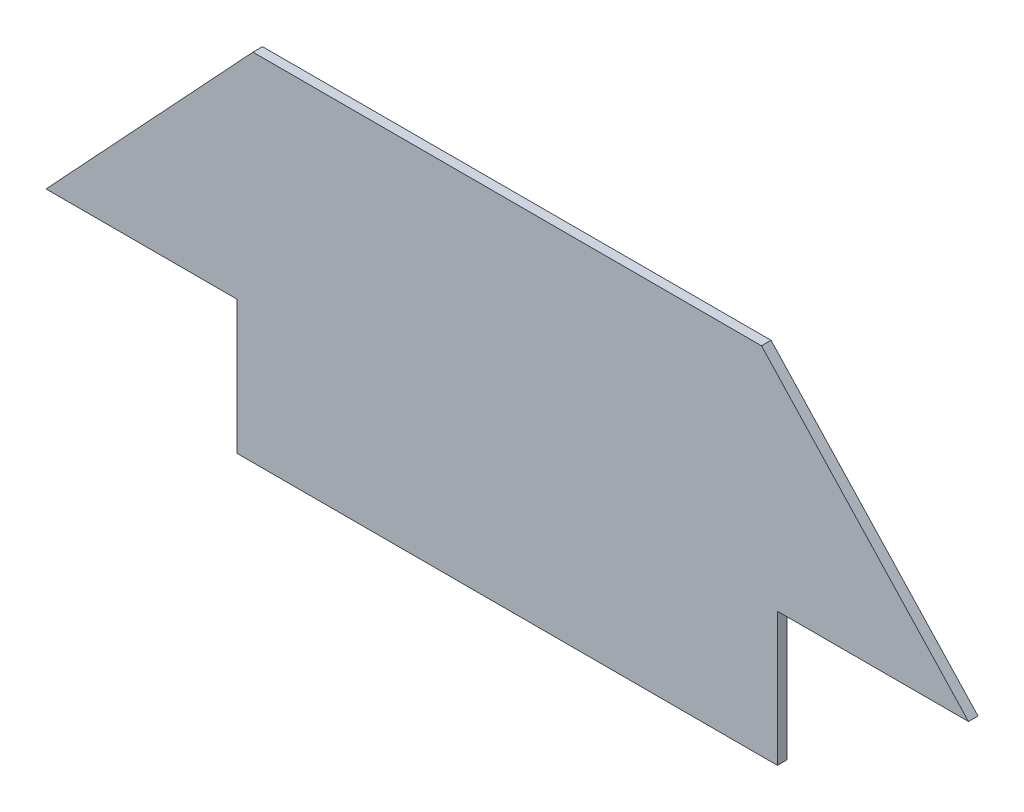
SolidWorks part; units mm, degrees
ref_plane "前视基准面" through (0, 0, 0) normal (0, 0, 1) x (1, 0, 0)
ref_plane "上视基准面" through (0, 0, 0) normal (0, 1, 0) x (1, 0, 0)
ref_plane "右视基准面" through (0, 0, 0) normal (1, 0, 0) x (0, 0, -1)
sketch "草图1" plane through (0, 0, 0) normal (0, 0, 1) x (1, 0, 0)
  line L0 (-80, 0) -> (80, 0)
  line L1 (80, 0) -> (145.1093, -69.8212)
  line L2 (145.1093, -69.8212) -> (85, -69.8212)
  line L3 (85, -69.8212) -> (85, -111.8212)
  line L4 (85, -111.8212) -> (-85, -111.8212)
  line L5 (0, -111.8212) -> (0, 0)
  line L6 (-85, -69.8212) -> (-85, -111.8212)
  line L7 (-145.1093, -69.8212) -> (-85, -69.8212)
  line L8 (-80, 0) -> (-145.1093, -69.8212)
  dimension "D1" = 80
  dimension "D2" = 133
  dimension "D3" = 85
  dimension "D4" = 70
  dimension "D5" = 42
extrude "凸台-拉伸1" add sketch "草图1" along normal blind 3 contours L0 L8 L7 L6 L4 L5 | L5 L4 L3 L2 L1 L0
